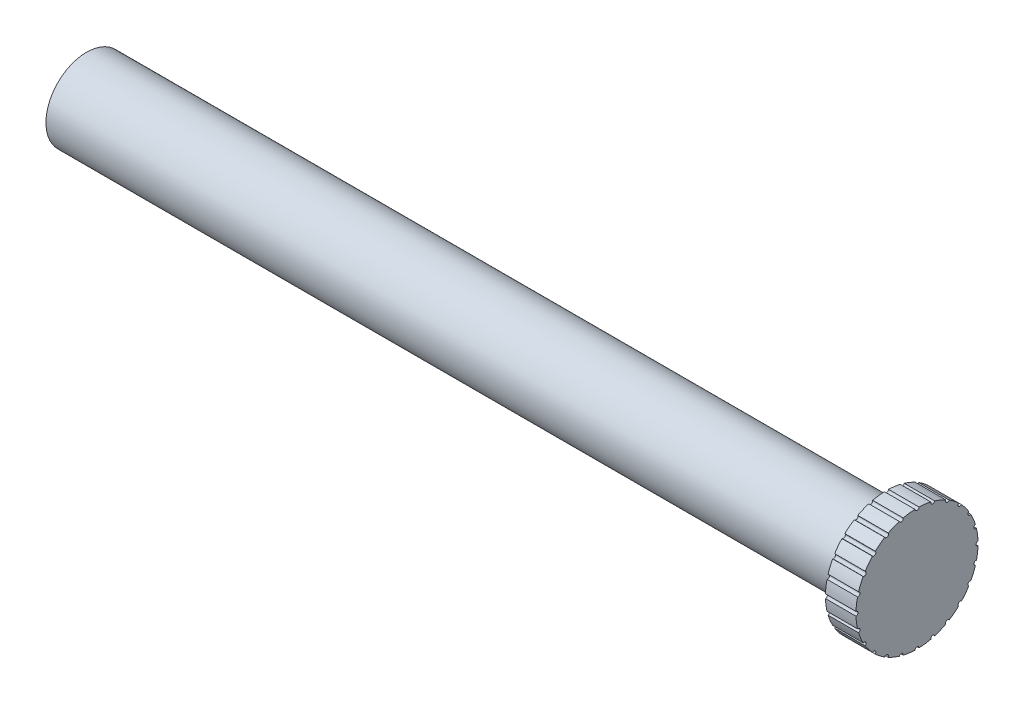
SolidWorks part; units mm, degrees
ref_plane "Front Plane" through (0, 0, 0) normal (0, 0, 1) x (1, 0, 0)
ref_plane "Top Plane" through (0, 0, 0) normal (0, 1, 0) x (1, 0, 0)
ref_plane "Right Plane" through (0, 0, 0) normal (1, 0, 0) x (0, 0, -1)
sketch "Sketch1" plane through (0, 0, 0) normal (1, 0, 0) x (0, 0, -1)
  circle A0 centre (0, 0) radius 4
  dimension "D1" = 8
extrude "Boss-Extrude1" add sketch "Sketch1" along normal blind 78.63
sketch "Sketch2" plane through (78.63, 0, 0) normal (1, 0, 0) x (0, 0, -1)
  circle A0 centre (0, 0) radius 6
  dimension "D1" = 12
extrude "Boss-Extrude2" add sketch "Sketch2" along normal blind 3
sketch "Sketch3" plane through (81.63, 0, 0) normal (1, 0, 0) x (0, 0, -1)
  circle A0 centre (0, 0) radius 6 construction
  circle A1 centre (0, 0) radius 6
  circle A2 centre (-6, 0) radius 0.2
  circle M2 centre (0, 0) radius 6
  dimension "D1" = 0.4
extrude "Cut-Extrude1" cut sketch "Sketch3" against normal up to next contours A2 M2 | A2 M2
pattern_circular "CirPattern1" count 25 every 15 about axis through (0, 0, 0) along (1, 0, 0) of "Cut-Extrude1"
